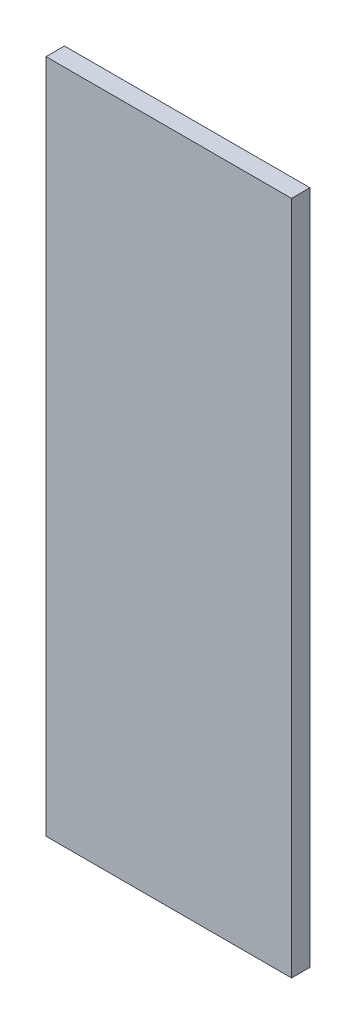
SolidWorks part; units mm, degrees
ref_plane "前视基准面" through (0, 0, 0) normal (0, 0, 1) x (1, 0, 0)
ref_plane "上视基准面" through (0, 0, 0) normal (0, 1, 0) x (1, 0, 0)
ref_plane "右视基准面" through (0, 0, 0) normal (1, 0, 0) x (0, 0, -1)
sketch "草图1" plane through (0, 0, 0) normal (0, 0, 1) x (1, 0, 0)
  line L1 (-10, -27.5) -> (10, -27.5)
  line L2 (-10, -27.5) -> (-10, 27.5)
  line L3 (-10, 27.5) -> (10, 27.5)
  line L4 (10, -27.5) -> (10, 27.5)
  line L5 (-10, -27.5) -> (10, 27.5) construction
  line L6 (-10, 27.5) -> (10, -27.5) construction
  point P0 (0, 0)
  dimension "D1" = 55
  dimension "D2" = 20
extrude "凸台-拉伸1" add sketch "草图1" along normal blind 1.5
